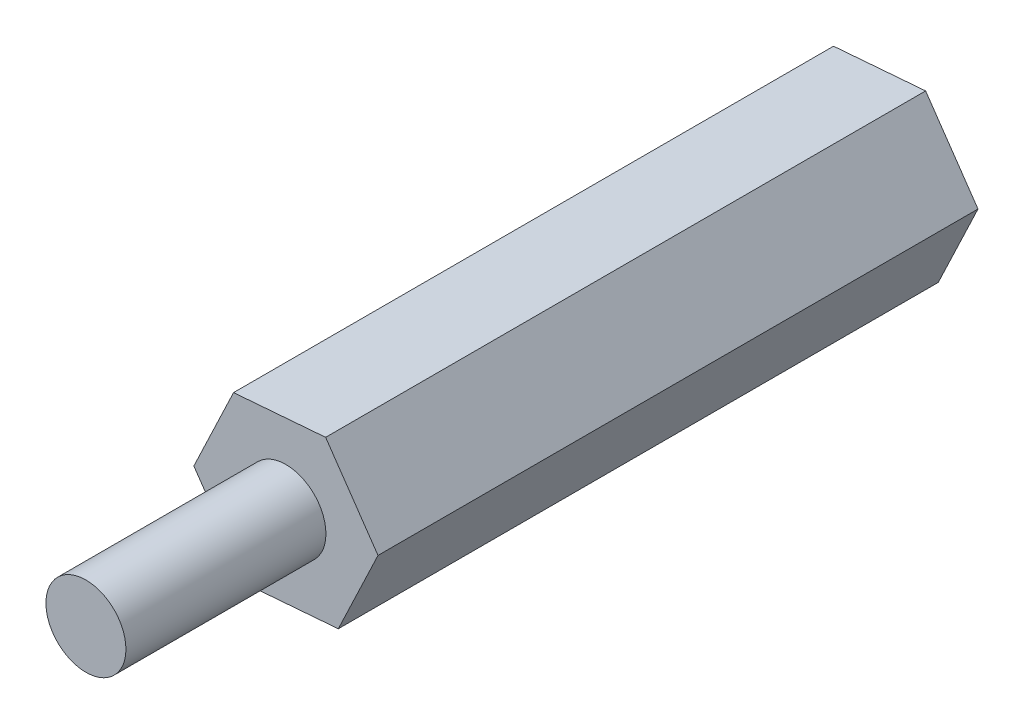
SolidWorks part; units mm, degrees
ref_plane "Plan de face" through (0, 0, 0) normal (0, 0, 1) x (1, 0, 0)
ref_plane "Plan de dessus" through (0, 0, 0) normal (0, 1, 0) x (1, 0, 0)
ref_plane "Plan de droite" through (0, 0, 0) normal (1, 0, 0) x (0, 0, -1)
sketch "Esquisse1" plane through (0, 0, 0) normal (0, 0, 1) x (1, 0, 0)
  line L1 (2.3021, 0.1829) -> (0.9927, 2.0852)
  line L2 (0.9927, 2.0852) -> (-1.3095, 1.9023)
  line L3 (-1.3095, 1.9023) -> (-2.3021, -0.1829)
  line L4 (-2.3021, -0.1829) -> (-0.9927, -2.0852)
  line L5 (-0.9927, -2.0852) -> (1.3095, -1.9023)
  line L6 (1.3095, -1.9023) -> (2.3021, 0.1829)
  circle A0 centre (0, 0) radius 2 construction
  dimension "D1" = 4
extrude "Boss.-Extru.1" add sketch "Esquisse1" along normal blind 15
sketch "Esquisse2" plane through (0, 0, 15) normal (0, 0, 1) x (1, 0, 0)
  circle A0 centre (0, 0) radius 1
  dimension "D1" = 2
extrude "Boss.-Extru.2" add sketch "Esquisse2" along normal blind 5
sketch "Esquisse3" plane through (0, 0, 0) normal (0, 0, -1) x (-1, 0, 0)
  circle A0 centre (0, 0) radius 1
  dimension "D1" = 2
extrude "Enlèv. mat.-Extru.1" cut sketch "Esquisse3" against normal blind 5
